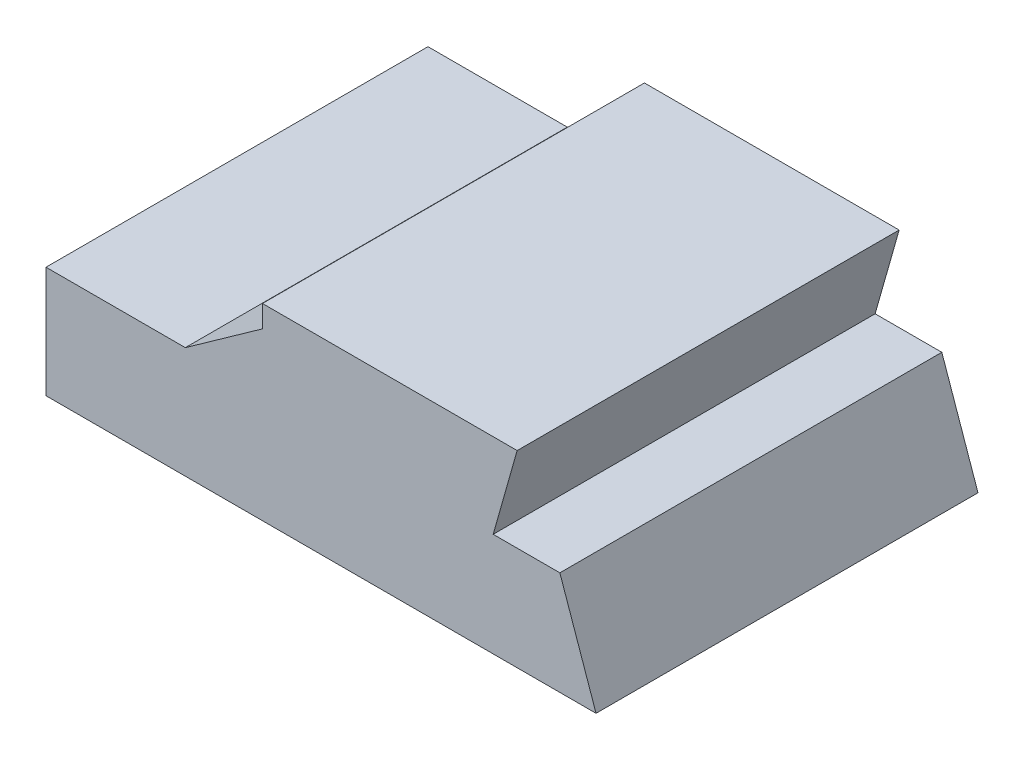
SolidWorks part; units mm, degrees
ref_plane "前视基准面" through (0, 0, 0) normal (0, 0, 1) x (1, 0, 0)
ref_plane "上视基准面" through (0, 0, 0) normal (0, 1, 0) x (1, 0, 0)
ref_plane "右视基准面" through (0, 0, 0) normal (1, 0, 0) x (0, 0, -1)
other "Configuration Table"
sketch "草图1" plane through (0, 0, 0) normal (0, 0, 1) x (1, 0, 0)
  line L0 (36.476, 29.1479) -> (56.672, 43.5041)
  line L1 (56.672, 93.3075) -> (92.4962, 93.3075)
  line L4 (0, 0) -> (144.001, 0)
  line L5 (144.001, 0) -> (134.5299, 27.1222)
  line L6 (117.0722, 27.1222) -> (123.3535, 49.2574)
  line L7 (134.5299, 27.1222) -> (117.0722, 27.1222)
  line L12 (0, 0) -> (0, 29.1479)
  line L16 (152.5757, 127.9319) -> (89.661, 135.7982)
  line L17 (88.5965, 127.2845) -> (126.841, 106.1775)
  line L20 (123.3535, 49.2574) -> (139.3032, 49.2574)
  line L22 (139.3032, 49.2574) -> (157.4114, 120.8535)
  line L23 (0, 29.1479) -> (36.476, 29.1479)
  line L26 (89.661, -27.3497) -> (89.661, 97.7464) construction
  line L27 (56.672, 43.5041) -> (56.672, 93.3075)
  arc A2 (92.4962, 93.3075) -> (81.3935, 122.6226) centre (18.9675, 82.2197) ccw
  arc A7 (157.4114, 120.8535) -> (152.5757, 127.9319) centre (151.866, 122.2561) ccw
  arc A8 (81.3935, 122.6226) -> (89.661, 135.7982) centre (88.5965, 127.2845) cw
  circle A15 centre (126.841, 106.1775) radius 27.2182
  dimension "D2" = 54.4365
  dimension "D3" = 74.36
  dimension "D4" = 5.72
  dimension "D5" = 8.58
  dimension "D1" = 106.1775
  dimension "D6" = 18.9675
  dimension "D7" = 36.476
  dimension "D8" = 56.672
  dimension "D9" = 81.3935
  dimension "D10" = 89.661
  dimension "D11" = 151.866
  dimension "D12" = 92.4962
  dimension "D13" = 117.0722
  dimension "D14" = 123.3535
  dimension "D15" = 126.841
  dimension "D16" = 134.5299
  dimension "D17" = 139.3032
  dimension "D18" = 144.001
  dimension "D19" = 27.1222
  dimension "D20" = 29.1479
  dimension "D21" = 157.4114
  dimension "D22" = 43.5041
  dimension "D23" = 49.2574
extrude "凸台-拉伸1" add sketch "草图1" along normal mid plane 100 contours A2 A8 L16 A7 L22 L20 L6 L7 L5 L4 L12 L23 L0 L27 L1 | A15
sketch "草图2" plane through (0, 0, 50) normal (0, 0, 1) x (1, 0, 0)
  line L0 (123.3535, 49.2574) -> (56.672, 49.2574)
  line L1 (56.672, 43.5041) -> (56.672, 93.3075) construction
split "分割1" trim tools "草图2" bodies to split 106 resulting bodies 107 108
delete or keep bodies "实体-删除/保留 1" type delete bodies bodies 107
